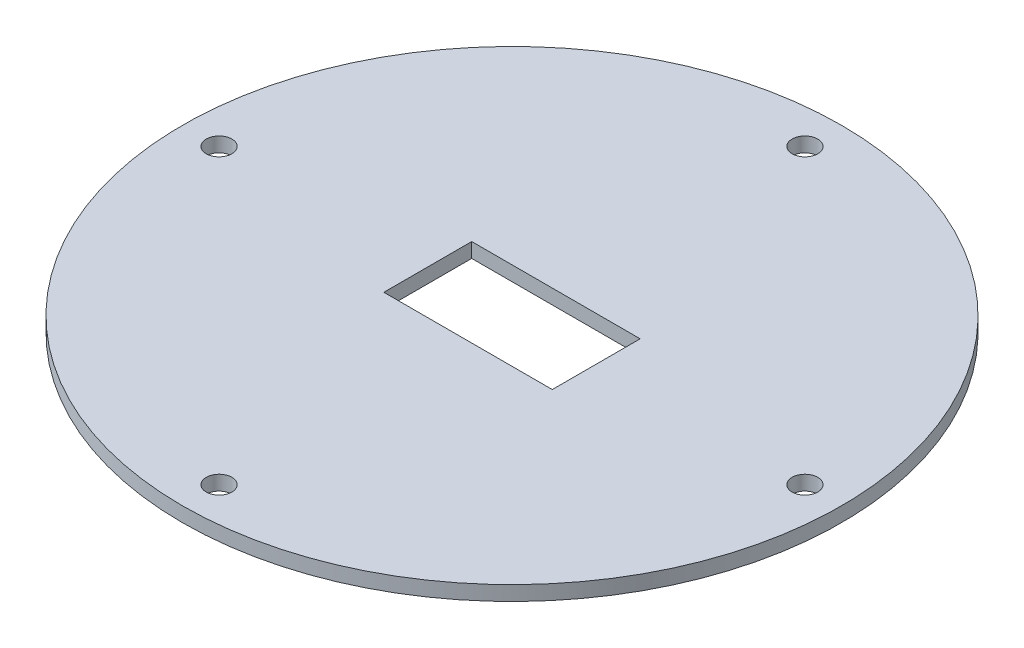
SolidWorks part; units mm, degrees
ref_plane "Front Plane" through (0, 0, 0) normal (0, 0, 1) x (1, 0, 0)
ref_plane "Top Plane" through (0, 0, 0) normal (0, 1, 0) x (1, 0, 0)
ref_plane "Right Plane" through (0, 0, 0) normal (1, 0, 0) x (0, 0, -1)
sketch "Sketch2" plane through (0, 0, 0) normal (0, 1, 0) x (1, 0, 0)
  circle A0 centre (0, 0) radius 45
  dimension "D1" = 90
extrude "Boss-Extrude1" add sketch "Sketch2" along normal blind 2
sketch "Sketch4" plane through (0, 2, 0) normal (0, 1, 0) x (1, 0, 0)
  circle A0 centre (0, 40) radius 1.75
  circle A1 centre (40, 0) radius 1.75
  circle A2 centre (0, -40) radius 1.75
  circle A3 centre (-40, 0) radius 1.75
  circle A4 centre (0, 0) radius 45 construction
  point P0 (0, 0)
  point P1 (0, 40)
  point P14 (0, 0)
  dimension "D2" = 3.5
  dimension "D1" = 40
  dimension "D3" = 4
extrude "Cut-Extrude1" cut sketch "Sketch4" against normal through all
sketch "Sketch5" plane through (0, 0, 0) normal (0, -1, 0) x (1, 0, 0)
  line L1 (11.5, -6) -> (-11.5, -6)
  line L2 (11.5, -6) -> (11.5, 6)
  line L3 (11.5, 6) -> (-11.5, 6)
  line L4 (-11.5, -6) -> (-11.5, 6)
  line L5 (11.5, -6) -> (-11.5, 6) construction
  line L6 (11.5, 6) -> (-11.5, -6) construction
  point P0 (0, 0)
  dimension "D1" = 12
  dimension "D2" = 23
extrude "Cut-Extrude2" cut sketch "Sketch5" against normal through all
